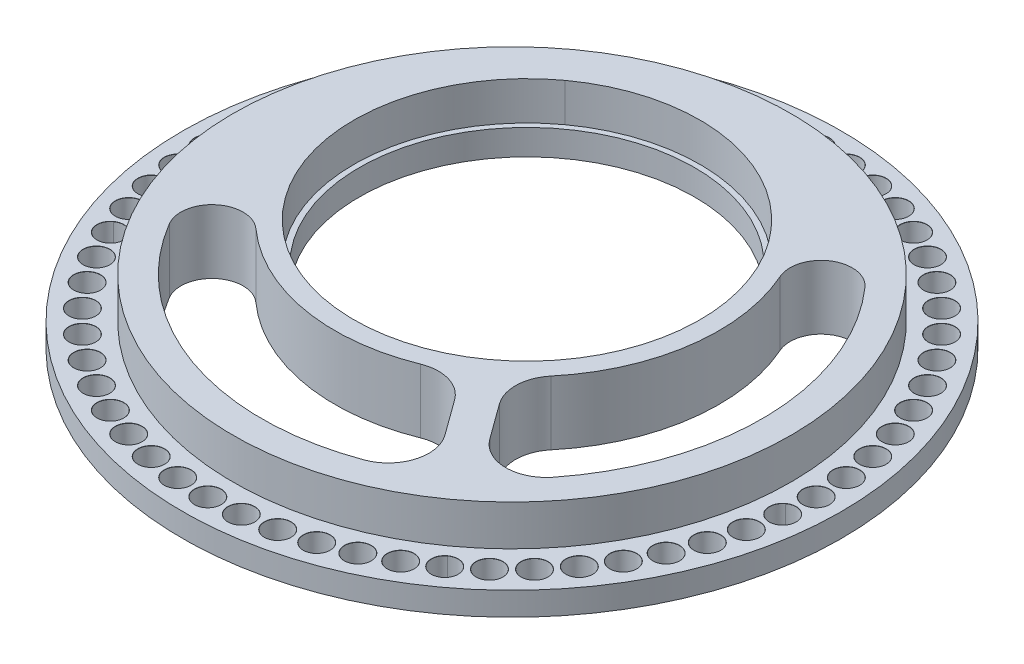
SolidWorks part; units mm, degrees
material "6061-T6 (SS)"
ref_plane "X-Y Datum" through (0, 0, 0) normal (0, 0, 1) x (1, 0, 0)
ref_plane "X-Z Datum" through (0, 0, 0) normal (0, 1, 0) x (1, 0, 0)
ref_plane "Y-Z Datum" through (0, 0, 0) normal (1, 0, 0) x (0, 0, -1)
sketch "Sketch1" plane through (0, 0, 0) normal (0, 1, 0) x (1, 0, 0)
  line L0 (0, 0) -> (0, -12.7) construction
  line L1 (0, -43.0151) -> (0, 43.0151) construction
  line L2 (0, 52.3875) -> (0, 61.9125) construction
  circle A0 centre (0, -12.7) radius 30.988
  circle A1 centre (0, 0) radius 52.3875 construction
  circle A2 centre (0, 0) radius 61.9125
  circle A3 centre (0, 0) radius 57.15 construction
  point P12 (0, 57.15)
  dimension "D2" = 61.976
  dimension "D3" = 104.775
  dimension "D4" = 123.825
  dimension "D5" = 114.3
  dimension "D1" = 12.7
extrude "Slotted-Body Extrude" add sketch "Sketch1" along normal blind 4.191 and the other way blind 0.2032
sketch "Sketch5" plane through (0, 4.191, 0) normal (0, 1, 0) x (1, 0, 0)
  circle A0 centre (0, 0) radius 52.3875 construction
  circle A1 centre (0, 0) radius 52.3875
extrude "Boss-Extrude3" add sketch "Sketch5" along normal blind 7.62
sketch "Sketch6" plane through (0, -0.2032, 0) normal (0, -1, 0) x (1, 0, 0)
  line L0 (0, -79.2756) -> (0, 0) construction
  line L2 (3.014, -37.9067) -> (3.014, -29.6741)
  line L4 (-3.014, -37.9067) -> (-3.014, -29.6741)
  circle A0 centre (0, 12.7) radius 30.988 construction
  circle A1 centre (0, 12.7) radius 30.988 construction
  circle A2 centre (0, 12.7) radius 32.512
  arc A9 (-35.2562, 5.0907) -> (-8.7792, -22.2832) centre (0, 12.7) ccw
  arc A10 (-46.783, 4.406) -> (-12.6921, -45.2435) centre (0, 0) ccw
  arc A11 (-46.783, 4.406) -> (-35.2562, 5.0907) centre (-40.9667, 3.8583) cw
  arc A19 (-3.014, -29.6741) -> (-8.7792, -22.2832) centre (-10.634, -29.6741) ccw
  arc A20 (-3.014, -37.9067) -> (-12.6921, -45.2435) centre (-10.634, -37.9067) cw
  circle A21 centre (0, 0) radius 61.9125 construction
  arc A27 (46.783, 4.406) -> (35.2562, 5.0907) centre (40.9667, 3.8583) ccw
  arc A28 (46.783, 4.406) -> (12.6921, -45.2435) centre (0, 0) cw
  arc A29 (3.014, -37.9067) -> (12.6921, -45.2435) centre (10.634, -37.9067) ccw
  arc A30 (3.014, -29.6741) -> (8.7792, -22.2832) centre (10.634, -29.6741) cw
  arc A31 (35.2562, 5.0907) -> (8.7792, -22.2832) centre (0, 12.7) cw
  point P30 (0, 0)
  point P31 (-3.014, -23.2419)
  point P32 (0, 0)
  point P36 (-3.014, -46.8932)
  dimension "D1" = 65.024
  dimension "D2" = 7.62
  dimension "D3" = 5.842
  dimension "D4" = 46.99
  dimension "D5" = 7.62
  dimension "D6" = 36.068
  dimension "D8" = 8.2326
extrude "Cut-Extrude5" cut sketch "Sketch6" against normal through all
sketch "Sketch8" plane through (0, -0.2032, 0) normal (0, -1, 0) x (1, 0, 0)
  circle A0 centre (0, 12.7) radius 32.512 construction
  circle A1 centre (0, 12.7) radius 32.512
  circle A2 centre (0, 12.7) radius 31.496
  dimension "D1" = 62.992
extrude "Boss-Extrude4" add sketch "Sketch8" against normal blind 4.795 separate body
hole_wizard "Ø5.0mm Dowel Hole2" positions "Sketch9" profile "Sketch10" hole size "Ø5.0" standard "ANSI Metric" end condition through all
sketch "Sketch9" plane through (0, 4.191, 0) normal (0, 1, 0) x (1, 0, 0)
  point P0 (0, 57.15)
sketch "Sketch10" plane through (0, 4.191, -57.15) normal (1, 0, 0) x (0, 0, 1)
  line L0 (0, 0) -> (0, 4.3942)
  line L1 (0, 4.3942) -> (2.5, 4.3942)
  line L2 (2.5, 4.3942) -> (2.5, 0.025)
  line L3 (2.5, 0.025) -> (2.525, 0)
  line L5 (2.525, 0) -> (0, 0)
  line L6 (-2.5, 0.025) -> (-2.525, 0) construction
  line L11 (0, -6.35) -> (0, 107.95) construction
  dimension "Thru Hole Dia." = 5
  dimension "Thru Hole Depth" = 4.3942
  dimension "Near C'Sink Dia." = 5.05
  dimension "Near C'Sink Angle" = 90
pattern_circular "CirPattern1" count 60 over 360 about axis through (0, 0, 0) along (0, 1, 0) of "Ø5.0mm Dowel Hole2"
ref_point "Point1"
ref_plane "Plane1" through (0, 0, 0) normal (1, 0, 0) x (0, 0, -1)
split line "Split Line1"
ref_point "Point2"
ref_point "Point3"
ref_point "Point4"
ref_point "Point5"
split line "Split Line2"
split line "Split Line3"
ref_plane "Plane2" through (-42.4707, 0, 0) normal (-1, 0, 0) x (0, 0, 1)
ref_plane "Plane3" through (55.9011, 0, 0) normal (-1, 0, 0) x (0, 0, 1)
split line "Split Line4"
split line "Split Line5"
sketch "Sketch17" plane through (0, 4.191, 0) normal (0, 1, 0) x (1, 0, 0)
  line L0 (-71.12, 66.6242) -> (71.12, 66.6242) construction
  line L1 (-71.12, -66.6242) -> (71.12, -66.6242) construction
  line L2 (-71.12, -66.6242) -> (-71.12, 66.6242) construction
  line L3 (-71.12, 66.6242) -> (71.12, 66.6242) construction
  line L4 (71.12, -66.6242) -> (71.12, 66.6242) construction
  line L5 (-71.12, -66.6242) -> (71.12, 66.6242) construction
  line L6 (-71.12, 66.6242) -> (-45.1836, 42.3273) construction
  line L7 (-71.12, 88.7603) -> (71.12, 88.7603)
  line L11 (-71.12, 59.8198) -> (-15.9607, 59.8198)
  line L12 (-71.12, 88.7603) -> (71.12, 88.7603)
  line L13 (-71.12, 88.7603) -> (-71.12, -66.6242)
  line L14 (-71.12, -66.6242) -> (71.12, -66.6242)
  line L15 (71.12, 88.7603) -> (71.12, -66.6242)
  line L16 (15.9607, 59.8198) -> (71.12, 59.8198)
  line L17 (0, 0) -> (71.12, -66.6242) construction
  arc A1 (15.9607, 59.8198) -> (-15.9607, 59.8198) centre (0, 0) ccw
  point P0 (0, 0)
  dimension "D1" = 142.24
  dimension "D2" = 133.2484
  dimension "D3" = 22.1361
sketch "Sketch13" plane through (0, 11.811, 0) normal (0, 1, 0) x (1, 0, 0)
  line L0 (3.014, 29.6741) -> (3.014, 37.9067) construction
  line L1 (-3.014, 37.9067) -> (-3.014, 29.6741) construction
  line L2 (3.014, 29.6741) -> (3.014, 37.9067) construction
  line L3 (-3.014, 37.9067) -> (-3.014, 29.6741) construction
  line L4 (-6.062, 37.9067) -> (-6.062, 29.6741)
  line L5 (6.062, 29.6741) -> (6.062, 37.9067)
  circle A0 centre (0, -12.7) radius 31.496 construction
  circle A1 centre (0, -12.7) radius 31.496 construction
  circle A2 centre (0, -12.7) radius 28.448
  arc A3 (35.2562, -5.0907) -> (46.783, -4.406) centre (40.9667, -3.8583) ccw construction
  arc A4 (35.2562, -5.0907) -> (8.7792, 22.2832) centre (0, -12.7) ccw construction
  arc A5 (3.014, 29.6741) -> (8.7792, 22.2832) centre (10.634, 29.6741) ccw construction
  arc A6 (46.783, -4.406) -> (12.6921, 45.2435) centre (0, 0) ccw construction
  arc A7 (12.6921, 45.2435) -> (3.014, 37.9067) centre (10.634, 37.9067) ccw construction
  arc A8 (-46.783, -4.406) -> (-35.2562, -5.0907) centre (-40.9667, -3.8583) ccw construction
  arc A9 (-8.7792, 22.2832) -> (-35.2562, -5.0907) centre (0, -12.7) ccw construction
  arc A10 (-8.7792, 22.2832) -> (-3.014, 29.6741) centre (-10.634, 29.6741) ccw construction
  arc A11 (-3.014, 37.9067) -> (-12.6921, 45.2435) centre (-10.634, 37.9067) ccw construction
  arc A12 (-12.6921, 45.2435) -> (-46.783, -4.406) centre (0, 0) ccw construction
  arc A13 (35.2562, -5.0907) -> (46.783, -4.406) centre (40.9667, -3.8583) ccw construction
  arc A14 (35.2562, -5.0907) -> (8.7792, 22.2832) centre (0, -12.7) ccw construction
  arc A15 (3.014, 29.6741) -> (8.7792, 22.2832) centre (10.634, 29.6741) ccw construction
  arc A16 (46.783, -4.406) -> (12.6921, 45.2435) centre (0, 0) ccw construction
  arc A17 (12.6921, 45.2435) -> (3.014, 37.9067) centre (10.634, 37.9067) ccw construction
  arc A18 (-46.783, -4.406) -> (-35.2562, -5.0907) centre (-40.9667, -3.8583) ccw construction
  arc A19 (-8.7792, 22.2832) -> (-35.2562, -5.0907) centre (0, -12.7) ccw construction
  arc A20 (-8.7792, 22.2832) -> (-3.014, 29.6741) centre (-10.634, 29.6741) ccw construction
  arc A21 (-3.014, 37.9067) -> (-12.6921, 45.2435) centre (-10.634, 37.9067) ccw construction
  arc A22 (-12.6921, 45.2435) -> (-46.783, -4.406) centre (0, 0) ccw construction
  arc A23 (-11.8689, 42.3087) -> (-43.7484, -4.1202) centre (0, 0) ccw
  arc A24 (-43.7484, -4.1202) -> (-38.2356, -4.4477) centre (-40.9667, -3.8583) ccw
  arc A25 (-9.5211, 25.2396) -> (-38.2356, -4.4477) centre (0, -12.7) ccw
  arc A26 (-9.5211, 25.2396) -> (-6.062, 29.6741) centre (-10.634, 29.6741) ccw
  arc A27 (-6.062, 37.9067) -> (-11.8689, 42.3087) centre (-10.634, 37.9067) ccw
  arc A28 (11.8689, 42.3087) -> (6.062, 37.9067) centre (10.634, 37.9067) ccw
  arc A29 (6.062, 29.6741) -> (9.5211, 25.2396) centre (10.634, 29.6741) ccw
  arc A30 (38.2356, -4.4477) -> (9.5211, 25.2396) centre (0, -12.7) ccw
  arc A31 (38.2356, -4.4477) -> (43.7484, -4.1202) centre (40.9667, -3.8583) ccw
  arc A32 (43.7484, -4.1202) -> (11.8689, 42.3087) centre (0, 0) ccw
  dimension "D1" = 3.048
  dimension "D2" = 3.048
sketch "Sketch11" plane through (0, -0.2032, 0) normal (0, -1, 0) x (1, 0, 0)
  line L1 (-61.9125, -61.9125) -> (61.9125, -61.9125)
  line L2 (-61.9125, -61.9125) -> (-61.9125, 61.9125)
  line L3 (-61.9125, 61.9125) -> (61.9125, 61.9125)
  line L4 (61.9125, -61.9125) -> (61.9125, 61.9125)
  line L5 (-61.9125, -61.9125) -> (61.9125, 61.9125) construction
  line L6 (-61.9125, 61.9125) -> (61.9125, -61.9125) construction
  circle A0 centre (0, 0) radius 61.9125 construction
  point P0 (0, 0)
sketch "Sketch14" plane through (0, 4.191, 0) normal (0, 1, 0) x (1, 0, 0)
  line L0 (-61.9125, 61.9125) -> (-61.9125, -61.9125) construction
  line L1 (-61.9125, 61.9125) -> (61.9125, 61.9125) construction
  line L2 (-61.9125, 61.9125) -> (-61.9125, -61.9125) construction
  line L3 (-61.9125, 61.9125) -> (61.9125, 61.9125) construction
  line L7 (-61.9125, -61.9125) -> (61.9125, 61.9125) construction
  line L8 (-61.9125, -61.9125) -> (61.9125, 61.9125)
  line L9 (0, -0.6085) -> (0, 49999.3915) construction
  circle A0 centre (0, 0) radius 61.9125 construction
  circle A2 centre (0, 0) radius 61.9125 construction
  arc A3 (-62.4462, 2.4493) -> (62.4462, 2.4493) centre (0, -0.6085) cw
  arc A4 (-62.4462, 2.4493) -> (-77.6194, 1.8864) centre (-70.0571, 2.822) cw
  arc A5 (0, 61.9125) -> (-3.7531, 76.0115) centre (-4.0041, 68.3957) ccw
  arc A6 (-77.6194, 1.8864) -> (-3.7531, 76.0115) centre (-26.007, 24.3209) cw
  arc A7 (2.4493, -62.4462) -> (1.8864, -77.6194) centre (2.822, -70.0571) ccw
  arc A8 (2.4493, -62.4462) -> (61.9125, 0) centre (-0.6085, 0) ccw
  arc A9 (61.9125, 0) -> (76.0115, -3.7531) centre (68.3957, -4.0041) cw
  arc A10 (1.8864, -77.6194) -> (76.0115, -3.7531) centre (24.3209, -26.007) ccw
  arc A11 (62.4462, 2.4493) -> (77.6194, 1.8864) centre (70.0571, 2.822) ccw
  arc A12 (0, 61.9125) -> (3.7531, 76.0115) centre (4.0041, 68.3957) cw
  arc A13 (77.6194, 1.8864) -> (3.7531, 76.0115) centre (26.007, 24.3209) ccw
  arc A14 (-2.4493, -62.4462) -> (-61.9125, 0) centre (0.6085, 0) cw
  arc A15 (-61.9125, 0) -> (-76.0115, -3.7531) centre (-68.3957, -4.0041) ccw
  arc A16 (-1.8864, -77.6194) -> (-76.0115, -3.7531) centre (-24.3209, -26.007) cw
  arc A17 (-2.4493, -62.4462) -> (-1.8864, -77.6194) centre (-2.822, -70.0571) cw
  point P13 (-61.9125, 0)
  dimension "D1" = 7.62
  dimension "D2" = 7.62
move or copy body "Body-Move/Copy1" bodies to move or copy 106 108 copy no rotation origin (0, 0, 0) rotation axis (0, -1, 0) rotation angle 144
ref_point "Point6"
